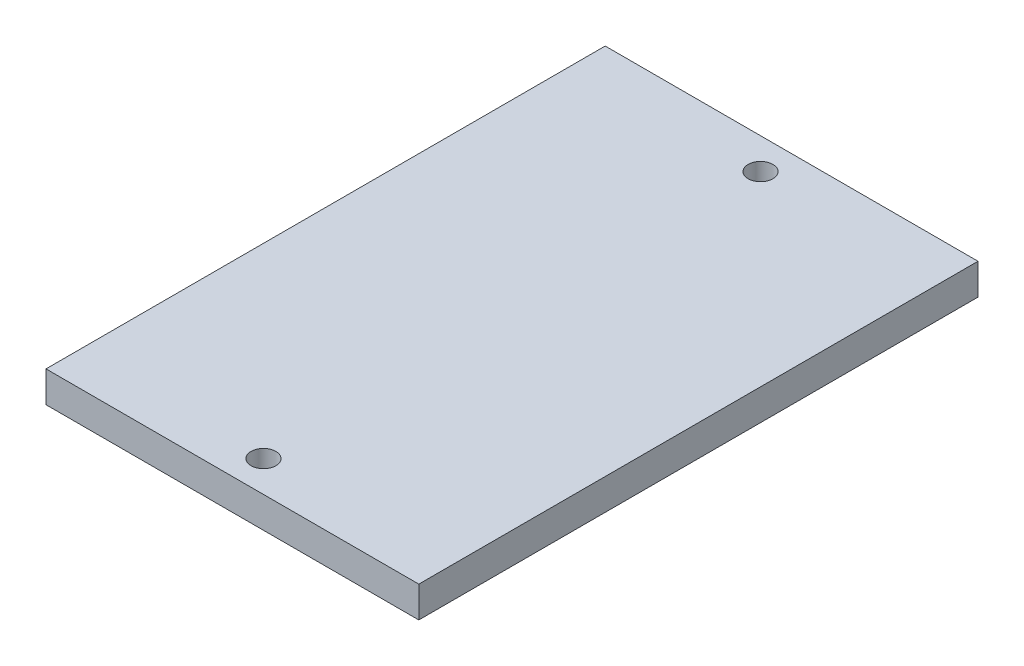
SolidWorks part; units mm, degrees
material "6061 Alloy"
ref_plane "Front" through (0, 0, 0) normal (0, 0, 1) x (1, 0, 0)
ref_plane "Top" through (0, 0, 0) normal (0, 1, 0) x (1, 0, 0)
ref_plane "Right" through (0, 0, 0) normal (1, 0, 0) x (0, 0, -1)
sketch "Sketch2" plane through (0, 0, 0) normal (0, 1, 0) x (1, 0, 0)
  line L0 (-3.4925, 0) -> (3.4925, 0) construction
  line L1 (-39.9715, -57.15) -> (36.2285, -57.15)
  line L2 (-39.9715, -57.15) -> (-39.9715, 57.15)
  line L3 (-39.9715, 57.15) -> (36.2285, 57.15)
  line L4 (36.2285, -57.15) -> (36.2285, 57.15)
  line L5 (-39.9715, -57.15) -> (36.2285, 57.15) construction
  line L6 (-39.9715, 57.15) -> (36.2285, -57.15) construction
  point P0 (-1.8715, 0)
  dimension "D1" = 76.2
  dimension "D2" = 114.3
extrude "Boss-Extrude1" add sketch "Sketch2" along normal blind 6.35
sketch "Sketch6" plane through (0, 6.35, 0) normal (0, 1, 0) x (1, 0, 0)
  line L0 (-39.9715, 0) -> (36.2285, 0) construction
  line L1 (-39.9715, 57.15) -> (-39.9715, -57.15) construction
  line L2 (36.2285, -57.15) -> (36.2285, 57.15) construction
  circle A0 centre (-1.8715, 50.8) radius 2.54
  circle A2 centre (-1.8715, -50.8) radius 2.54
  point P4 (-39.9715, 57.15)
extrude "Cut-Extrude3" cut sketch "Sketch6" against normal blind 9.525
